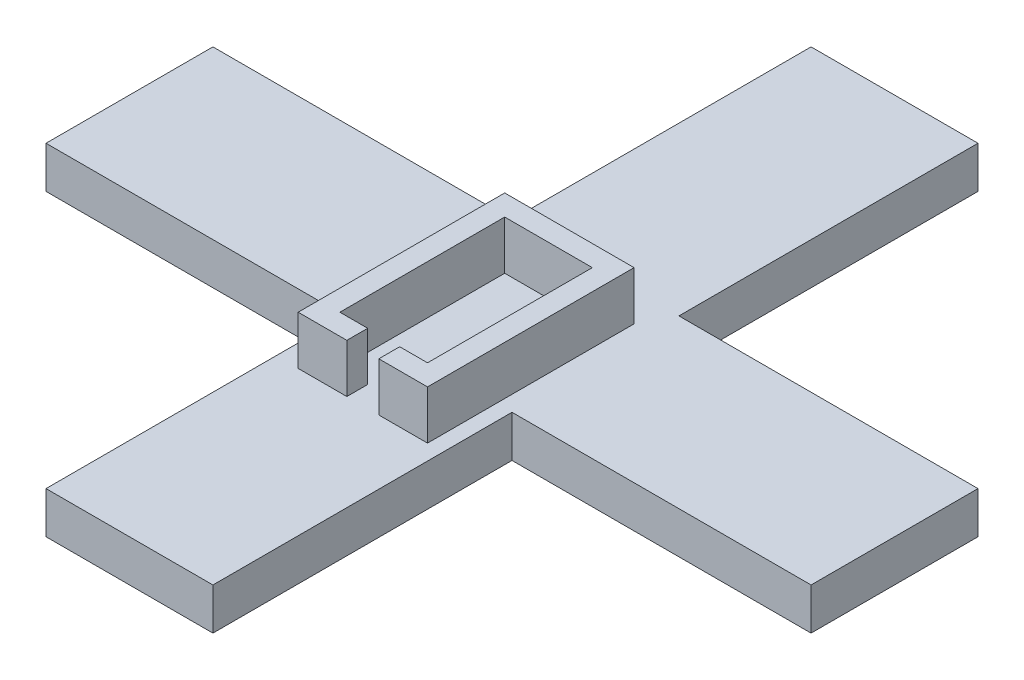
SolidWorks part; units mm, degrees
ref_plane "Front Plane" through (0, 0, 0) normal (0, 0, 1) x (1, 0, 0)
ref_plane "Top Plane" through (0, 0, 0) normal (0, 1, 0) x (1, 0, 0)
ref_plane "Right Plane" through (0, 0, 0) normal (1, 0, 0) x (0, 0, -1)
sketch "Sketch16" plane through (0, 0, 0) normal (0, 1, 0) x (1, 0, 0)
  line L0 (-8.8343, 7.7873) -> (9.7657, 7.7873)
  line L1 (9.7657, 7.7873) -> (9.7657, -21.9127)
  line L2 (9.7657, -21.9127) -> (2.7657, -21.9127)
  line L3 (2.7657, -21.9127) -> (2.7657, -18.9127)
  line L4 (2.7657, -18.9127) -> (6.7657, -18.9127)
  line L5 (6.7657, -18.9127) -> (6.7657, 4.7873)
  line L6 (6.7657, 4.7873) -> (-5.8343, 4.7873)
  line L7 (-5.8343, 4.7873) -> (-5.8343, -18.9127)
  line L8 (-5.8343, -18.9127) -> (-1.8343, -18.9127)
  line L9 (-1.8343, -18.9127) -> (-1.8343, -21.9127)
  line L10 (-1.8343, -21.9127) -> (-8.8343, -21.9127)
  line L11 (-8.8343, -21.9127) -> (-8.8343, 7.7873)
  dimension "D1" = 12.6
  dimension "D2" = 4
  dimension "D3" = 23.7
  dimension "D4" = 3
  dimension "D5" = 3
  dimension "D6" = 3
sketch "Sketch21" plane through (0, 0, 0) normal (0, 1, 0) x (1, 0, 0)
  line L0 (0, 55) -> (-12, 55)
  line L1 (-12, 55) -> (-12, 12)
  line L2 (-12, 12) -> (-55, 12)
  line L4 (-55, -12) -> (-12, -12)
  line L5 (-12, -12) -> (-12, -55)
  line L6 (-12, -55) -> (0, -55)
  line L7 (0, -55) -> (12, -55)
  line L8 (12, -55) -> (12, -12)
  line L9 (12, -12) -> (55, -12)
  line L11 (55, 12) -> (12, 12)
  line L12 (12, 12) -> (12, 55)
  line L13 (12, 55) -> (0, 55)
  line L14 (-55, 0) -> (-55, 12)
  line L15 (-55, -12) -> (-55, 0)
  line L18 (55, 0) -> (55, 12)
  line L20 (55, 0) -> (55, -12)
  point P18 (-20.1213, -14.3529)
  dimension "D1" = 43
  dimension "D2" = 12
  dimension "D3" = 12
  dimension "D4" = 12
extrude "Boss-Extrude18" add sketch "Sketch21" along normal blind 6
sketch "Sketch22" plane through (0, 0, 0) normal (0, 1, 0) x (1, 0, 0)
  circle A0 centre (0, 0) radius 12
  dimension "D1" = 24
extrude "Boss-Extrude19" add sketch "Sketch22" along normal blind 6
extrude "Boss-Extrude20" add sketch "Sketch16" along normal blind 13
